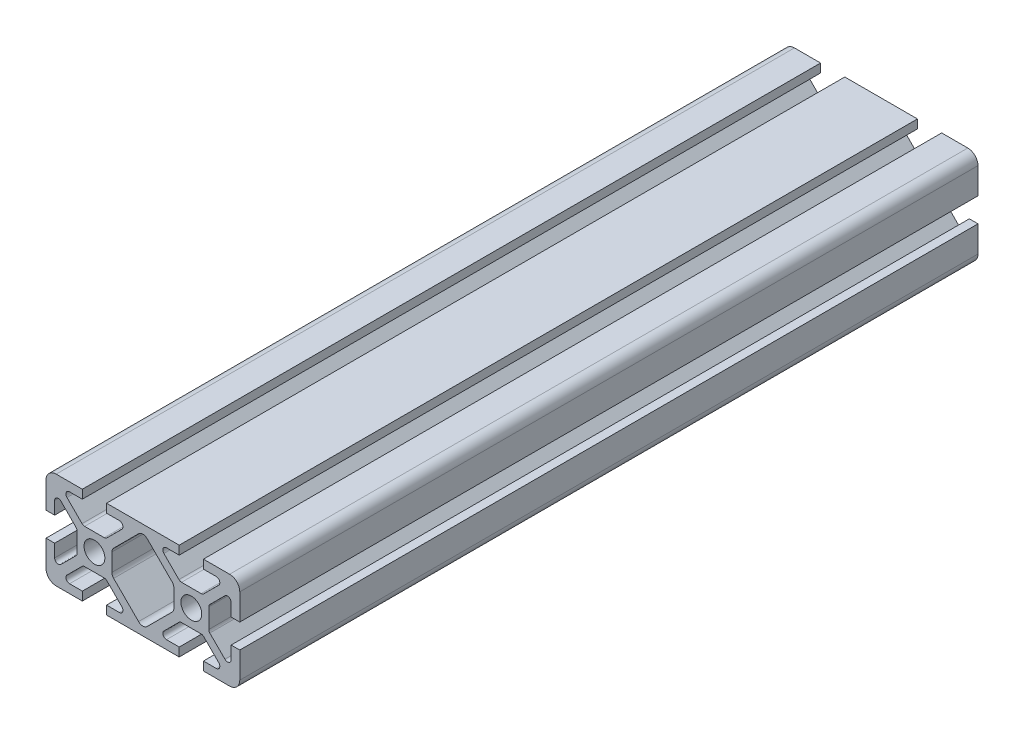
SolidWorks part; units mm, degrees
ref_plane "Front Plane" through (0, 0, 0) normal (0, 0, 1) x (1, 0, 0)
ref_plane "Top Plane" through (0, 0, 0) normal (0, 1, 0) x (1, 0, 0)
ref_plane "Right Plane" through (0, 0, 0) normal (1, 0, 0) x (0, 0, -1)
sketch "Sketch1" plane through (0, 0, 0) normal (0, 0, 1) x (1, 0, 0)
  line L0 (10, 10) -> (10, -10) construction
  line L1 (-20, 0) -> (20, 0) construction
  line L2 (12.5, -10) -> (20, -10)
  line L3 (20, -10) -> (20, -2.5)
  line L4 (12.5, -10) -> (12.5, -8.2134)
  line L5 (12.5, -8.2134) -> (16.95, -8.2134)
  line L6 (16.95, -8.2134) -> (12.3366, -3.6)
  line L7 (10, 0) -> (20, -10) construction
  line L8 (20, -2.5) -> (18.2134, -2.5)
  line L9 (18.2134, -2.5) -> (18.2134, -6.95)
  line L10 (18.2134, -6.95) -> (13.6, -2.3366)
  line L11 (15.9067, -4.6433) -> (14.6433, -5.9067) construction
  line L12 (0, 10) -> (0, -10) construction
  line L13 (0, -10) -> (-20, -10) construction
  line L14 (-10, 10) -> (10, 10) construction
  line L15 (20, 2.5) -> (20, -2.5) construction
  circle A0 centre (10, 0) radius 2.15
  arc A1 (15.5015, -8.2134) -> (15.9257, -7.1891) centre (15.5015, -7.6134) ccw construction
  point P8 (10, -3.6)
  point P16 (15.275, -5.275)
  point P30 (20, 0)
  dimension "Center Hole Diameter" = 4.3
  dimension "D3" = 0.6
  dimension "Rail Width" = 20
  dimension "T-Slot Width" = 5
  dimension "Slot Depth" = 6.4
  dimension "Rail Height" = 40
  dimension "Inner Slot Width" = 13.9
  dimension "Hole Spacing" = 20
sketch "Sketch2" plane through (0, 0, 0) normal (1, 0, 0) x (0, 0, -1)
  line L0 (-76.2, -10) -> (76.2, -10) construction
  line L1 (-36.2, 0) -> (36.2, 0) construction
  point P6 (-36.2, 0)
  point P8 (36.2, 0)
  dimension "Length" = 152.4
  dimension "D1" = 40
sketch "Sketch3" plane through (0, 0, 0) normal (0, 0, 1) x (1, 0, 0)
  line L0 (12.5, -10) -> (17.9, -10)
  line L1 (12.5, -10) -> (20, -10) construction
  line L2 (12.5, -10) -> (12.5, -8.2134) construction
  line L3 (12.5, -8.2134) -> (16.95, -8.2134) construction
  line L4 (12.5, -8.2134) -> (12.5, -10)
  line L5 (12.5, -8.2134) -> (16.95, -8.2134)
  line L6 (10, -3.6) -> (12.3366, -3.6)
  line L7 (16.95, -8.2134) -> (12.3366, -3.6) construction
  line L8 (12.3366, -3.6) -> (16.95, -8.2134)
  line L9 (20, -10) -> (20, -2.5) construction
  line L10 (18.2134, -6.95) -> (13.6, -2.3366) construction
  line L11 (18.2134, -2.5) -> (18.2134, -6.95) construction
  line L12 (18.2134, -6.95) -> (18.2134, -2.5)
  line L13 (20, -2.5) -> (18.2134, -2.5) construction
  line L14 (18.2134, -2.5) -> (20, -2.5)
  line L15 (20, -2.5) -> (20, -7.9)
  line L16 (18.2134, -6.95) -> (13.6, -2.3366)
  line L17 (13.6, 0) -> (13.6, -2.3366)
  line L18 (-20, 0) -> (20, 0) construction
  line L19 (10, -3.6) -> (10, -2.15)
  line L20 (10, 10) -> (10, -10) construction
  line L21 (13.6, 0) -> (12.15, 0)
  arc A5 (17.9, -10) -> (20, -7.9) centre (17.9, -7.9) ccw
  circle A10 centre (10, 0) radius 2.15 construction
  arc A11 (10, -2.15) -> (12.15, 0) centre (10, 0) ccw
  dimension "D1" = 2.1
extrude "Boss-Extrude1" add sketch "Sketch3" along normal mid plane 152.4
sketch "Sketch4" plane through (0, 0, 0) normal (0, 0, 1) x (1, 0, 0)
  line L0 (10, -3.6) -> (7.6634, -3.6)
  line L4 (7.6634, -3.6) -> (3.05, -8.2134)
  line L5 (3.05, -8.2134) -> (7.5, -8.2134)
  line L6 (7.5, -8.2134) -> (7.5, -10)
  line L18 (7.5, -10) -> (0, -10)
  line L19 (12.5, -10) -> (12.5, -8.2134) construction
  line L20 (12.5, -8.2134) -> (16.95, -8.2134) construction
  line L21 (10, -3.6) -> (12.3366, -3.6) construction
  line L22 (16.95, -8.2134) -> (12.3366, -3.6) construction
  line L23 (0, -8.7366) -> (6.4, -2.3366)
  line L24 (0, 10) -> (0, -10) construction
  line L25 (6.4, -2.3366) -> (6.4, 0)
  line L26 (-20, 0) -> (20, 0) construction
  line L27 (6.4, 0) -> (7.85, 0)
  line L28 (13.6, 0) -> (12.15, 0) construction
  line L29 (0, -8.7366) -> (0, -10)
  line L30 (10, -2.15) -> (10, -3.6)
  circle A4 centre (10, 0) radius 2.15 construction
  arc A5 (7.85, 0) -> (10, -2.15) centre (10, 0) ccw
extrude "Boss-Extrude2" add sketch "Sketch4" along normal mid plane 152.4
mirror "Mirror1" about plane through (0, 0, 0) normal (1, 0, 0) of bodies 137 134
mirror "Mirror2" about plane through (0, 0, 0) normal (0, 1, 0) of bodies 135
fillet "Fillet1" radius 0.75 24 edges at (-7.6634, -3.6, 0) (-12.3366, -3.6, 0) (12.3366, -3.6, 0) (7.6634, -3.6, 0) (-3.05, -8.2134, 0) (-18.2134, -6.95, 0) (-16.95, -8.2134, 0) (-13.6, -2.3366, 0) (-18.2134, 6.95, 0) (-16.95, 8.2134, 0) (-12.3366, 3.6, 0) (-7.6634, 3.6, 0) (-13.6, 2.3366, 0) (-3.05, 8.2134, 0) (3.05, 8.2134, 0) (13.6, -2.3366, 0) (18.2134, 6.95, 0) (13.6, 2.3366, 0) (7.6634, 3.6, 0) (12.3366, 3.6, 0) (16.95, 8.2134, 0) (18.2134, -6.95, 0) (16.95, -8.2134, 0) (3.05, -8.2134, 0)
fillet "Fillet2" radius 1.25 6 edges at (0, -8.7366, 0) (-6.4, -2.3366, 0) (0, 8.7366, 0) (-6.4, 2.3366, 0) (6.4, -2.3366, 0) (6.4, 2.3366, 0)
equation "\"D1@Sketch3\" = \"D3@Sketch1\" * 3.5"
equation "\"D1@Boss-Extrude1\" = \"Length@Sketch2\""
equation "\"D1@Boss-Extrude2\" = \"Length@Sketch2\""
equation "\"D1@Sketch2\"=\"Rail Height@Sketch1\""
